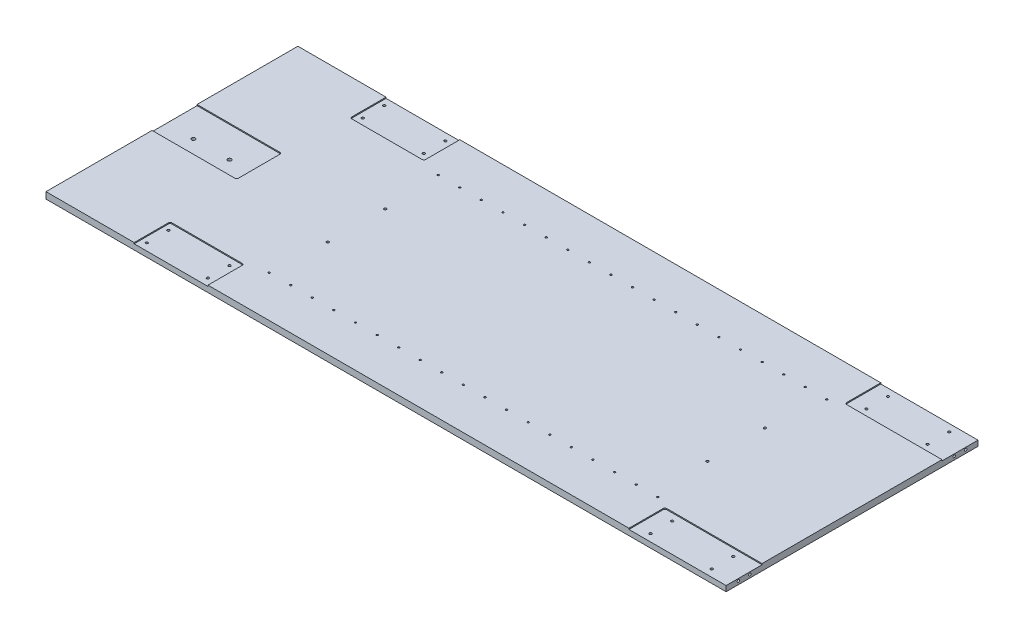
SolidWorks part; units mm, degrees
ref_plane "Front" through (0, 0, 0) normal (0, 0, 1) x (1, 0, 0)
ref_plane "Top" through (0, 0, 0) normal (0, 1, 0) x (1, 0, 0)
ref_plane "Right" through (0, 0, 0) normal (1, 0, 0) x (0, 0, -1)
sketch "Sketch4" plane through (0, 0, 0) normal (0, 1, 0) x (1, 0, 0)
  line L1 (0, 0) -> (1890, 0)
  line L2 (0, 0) -> (0, -700)
  line L3 (0, -700) -> (1890, -700)
  line L4 (1890, 0) -> (1890, -700)
  dimension "D1" = 700
  dimension "D2" = 1890
extrude "Boss-Extrude2" add sketch "Sketch4" against normal blind 18
sketch "Sketch5" plane through (0, 0, 0) normal (0, 1, 0) x (1, 0, 0)
  line L0 (0, 0) -> (0, -700) construction
  line L5 (0, -700) -> (1890, -700) construction
  line L6 (245, -700) -> (450, -700)
  line L7 (245, -700) -> (245, -600)
  line L8 (245, -600) -> (450, -600)
  line L9 (450, -700) -> (450, -600)
  line L10 (1890, 0) -> (0, 0) construction
  line L11 (1890, -700) -> (1620, -700)
  line L12 (1890, -700) -> (1890, -600)
  line L13 (1890, -600) -> (1620, -600)
  line L14 (1620, -700) -> (1620, -600)
  line L15 (1890, 0) -> (1620, 0)
  line L16 (1890, 0) -> (1890, -100)
  line L17 (1890, -100) -> (1620, -100)
  line L18 (1620, 0) -> (1620, -100)
  line L19 (245, 0) -> (450, 0)
  line L20 (245, 0) -> (245, -100)
  line L21 (245, -100) -> (450, -100)
  line L22 (450, 0) -> (450, -100)
  dimension "D1" = 100
  dimension "D2" = 500
  dimension "D3" = 1170
  dimension "D4" = 205
  dimension "D7" = 245
extrude "Cut-Extrude1" cut sketch "Sketch5" against normal blind 3
sketch "Sketch22" plane through (0, 0, 0) normal (0, 1, 0) x (1, 0, 0)
  line L1 (0, -280.25) -> (235, -280.25)
  line L2 (0, -280.25) -> (0, -405.25)
  line L3 (0, -405.25) -> (235, -405.25)
  line L4 (235, -280.25) -> (235, -405.25)
  line L5 (245, 0) -> (0, 0) construction
  line L6 (0, 0) -> (0, -700) construction
  dimension "D1" = 280.25
  dimension "D2" = 125
  dimension "D3" = 235
extrude "Cut-Extrude2" cut sketch "Sketch22" against normal blind 3
hole_wizard "M12x1.75 Tapped Hole1" positions "Sketch7" profile "Sketch6" tap size "M12x1.75" standard "JIS" end condition through all
sketch "Sketch7" plane through (-24.0384, -3, -27.6565) normal (0, 1, 0) x (-1, 0, 0)
  line L0 (-269.0384, 27.6565) -> (-24.0384, 27.6565) construction
  line L3 (-24.0384, 27.6565) -> (-24.0384, 307.9065) construction
  point P0 (-99.0384, 392.9565)
  point P1 (-199.0384, 392.9565)
  dimension "D1" = 365.3
  dimension "D2" = 100
  dimension "D3" = 75
sketch "Sketch6" plane through (75, -3, 365.3) normal (1, 0, 0) x (0, 0, 1)
  line L0 (0, 0) -> (0, 15)
  line L1 (0, 15) -> (5.1, 15)
  line L2 (5.1, 15) -> (5.1, 0)
  line L5 (5.1, 0) -> (0, 0)
  line L11 (0, -6.35) -> (0, 107.95) construction
  dimension "Thru Tap Drill Dia." = 10.2
  dimension "Thru Tap Drill Depth" = 15
cosmetic thread "Hole Thread2" parameters "D2"=12
cosmetic thread "Hole Thread3" parameters "D2"=12
hole_wizard "M8x1.25 Tapped Hole1" positions "Sketch9" profile "Sketch8" tap size "M8x1.25" standard "JIS" end condition through all
sketch "Sketch9" plane through (0, -3, 0) normal (0, 1, 0) x (-1, 0, 0)
  line L0 (-245, 0) -> (0, 0) construction
  line L2 (0, 0) -> (0, 280.25) construction
  point P0 (-260, 80)
  point P1 (-260, 20)
  point P3 (-430, 20)
  point P5 (-430, 80)
  dimension "D1" = 20
  dimension "D2" = 60
  dimension "D3" = 260
  dimension "D4" = 170
sketch "Sketch8" plane through (260, -3, 80) normal (1, 0, 0) x (0, 0, 1)
  line L0 (0, 0) -> (0, 15)
  line L1 (0, 15) -> (3.4, 15)
  line L2 (3.4, 15) -> (3.4, 0)
  line L5 (3.4, 0) -> (0, 0)
  line L11 (0, -6.35) -> (0, 107.95) construction
  dimension "Thru Tap Drill Dia." = 6.8
  dimension "Thru Tap Drill Depth" = 15
cosmetic thread "Hole Thread4" parameters "D2"=8
cosmetic thread "Hole Thread5" parameters "D2"=8
cosmetic thread "Hole Thread6" parameters "D2"=8
cosmetic thread "Hole Thread7" parameters "D2"=8
pattern_linear "LPattern1" count 2 spacing 1400 along (1, 0, 0) count 2 spacing 600 along (0, 0, 1) of "M8x1.25 Tapped Hole1"
hole_wizard "M8x1.25 Tapped Hole2" positions "Sketch13" profile "Sketch12" tap size "M8x1.25" standard "JIS" end condition through all
sketch "Sketch13" plane through (0, 0, 0) normal (0, 1, 0) x (-1, 0, 0)
  line L6 (0, 0) -> (0, 280.25) construction
  line L7 (-245, 0) -> (0, 0) construction
  point P0 (-513, 270)
  point P1 (-513, 430)
  point P3 (-1568, 270)
  point P5 (-1568, 430)
  dimension "D1" = 270
  dimension "D2" = 513
  dimension "D3" = 160
  dimension "D4" = 1055
sketch "Sketch12" plane through (513, 0, 270) normal (1, 0, 0) x (0, 0, 1)
  line L0 (0, 0) -> (0, 18)
  line L1 (0, 18) -> (3.4, 18)
  line L2 (3.4, 18) -> (3.4, 0)
  line L5 (3.4, 0) -> (0, 0)
  line L11 (0, -6.35) -> (0, 107.95) construction
  dimension "Thru Tap Drill Dia." = 6.8
  dimension "Thru Tap Drill Depth" = 18
cosmetic thread "Hole Thread8" parameters "D2"=8
cosmetic thread "Hole Thread9" parameters "D2"=8
cosmetic thread "Hole Thread10" parameters "D2"=8
cosmetic thread "Hole Thread11" parameters "D2"=8
hole_wizard "M6x1.0 Tapped Hole3" positions "Sketch17" profile "Sketch16" tap size "M6x1.0" standard "JIS" end condition through all
sketch "Sketch17" plane through (0, 0, 0) normal (0, 1, 0) x (-1, 0, 0)
  line L0 (0, 0) -> (0, 280.25) construction
  line L1 (-245, 0) -> (0, 0) construction
  point P0 (-505, 115)
  point P6 (-505, 585)
  dimension "D1" = 505
  dimension "D2" = 115
  dimension "D3" = 470
sketch "Sketch16" plane through (505, 0, 115) normal (1, 0, 0) x (0, 0, 1)
  line L0 (0, 0) -> (0, 18)
  line L1 (0, 18) -> (2.5, 18)
  line L2 (2.5, 18) -> (2.5, 0)
  line L5 (2.5, 0) -> (0, 0)
  line L11 (0, -6.35) -> (0, 107.95) construction
  dimension "Thru Tap Drill Dia." = 5
  dimension "Thru Tap Drill Depth" = 18
cosmetic thread "Hole Thread13" parameters "D2"=6
cosmetic thread "Hole Thread14" parameters "D2"=6
pattern_linear "LPattern3" count 19 spacing 60 along (1, 0, 0) of "M6x1.0 Tapped Hole3"
hole_wizard "M8x1.25 Tapped Hole3" positions "Sketch19" profile "Sketch18" tap size "M8x1.25" standard "JIS"
sketch "Sketch19" plane through (1890, 0, 0) normal (1, 0, 0) x (0, 0, -1)
  line L0 (0, -18) -> (0, -3) construction
  line L1 (0, 0) -> (-100, 0) construction
  point P0 (-66, -9)
  point P1 (-666, -9)
  point P3 (-634, -9)
  point P7 (-34, -9)
  dimension "D1" = 34
  dimension "D2" = 32
  dimension "D3" = 568
  dimension "D4" = 32
  dimension "D5" = 9
sketch "Sketch18" plane through (1890, -9, 66) normal (0, 1, 0) x (0, 0, -1)
  line L0 (0, 0) -> (0, 24.2929)
  line L1 (0, 24.2929) -> (3.4, 22.25)
  line L2 (3.4, 22.25) -> (3.4, 0)
  line L5 (3.4, 0) -> (0, 0)
  line L10 (0, 24.2929) -> (-3.4, 22.25) construction
  line L11 (0, -6.35) -> (0, 107.95) construction
  dimension "Tap Drill Dia." = 6.8
  dimension "Tap Drill Depth" = 22.25
  dimension "Drill Angle" = 118
cosmetic thread "Hole Thread15" parameters "D1"=16, "D2"=8
cosmetic thread "Hole Thread16" parameters "D1"=16, "D2"=8
cosmetic thread "Hole Thread17" parameters "D1"=16, "D2"=8
cosmetic thread "Hole Thread18" parameters "D1"=16, "D2"=8
hole_wizard "M8x1.25 Tapped Hole4" positions "Sketch21" profile "Sketch20" tap size "M8x1.25" standard "JIS"
sketch "Sketch21" plane through (0, 0, 0) normal (-1, 0, 0) x (0, 0, 1)
  line L0 (0, -18) -> (0, 0) construction
  line L1 (405.25, 0) -> (700, 0) construction
  point P0 (319.25, -9)
  point P1 (351.25, -9)
  dimension "D1" = 319.25
  dimension "D2" = 32
  dimension "D3" = 9
sketch "Sketch20" plane through (0, -9, 319.25) normal (0, 1, 0) x (0, 0, 1)
  line L0 (0, 0) -> (0, 24.2929)
  line L1 (0, 24.2929) -> (3.4, 22.25)
  line L2 (3.4, 22.25) -> (3.4, 0)
  line L5 (3.4, 0) -> (0, 0)
  line L10 (0, 24.2929) -> (-3.4, 22.25) construction
  line L11 (0, -6.35) -> (0, 107.95) construction
  dimension "Tap Drill Dia." = 6.8
  dimension "Tap Drill Depth" = 22.25
  dimension "Drill Angle" = 118
cosmetic thread "Hole Thread19" parameters "D1"=16, "D2"=8
cosmetic thread "Hole Thread20" parameters "D1"=16, "D2"=8
fillet "Fillet1" radius 5 6 edges at (1620, -1.5, 100) (1620, -1.5, 600) (245, -1.5, 600) (450, -1.5, 600) (450, -1.5, 100) (245, -1.5, 100)
fillet "Fillet2" radius 5 2 edges at (235, -1.5, 405.25) (235, -1.5, 280.25)
